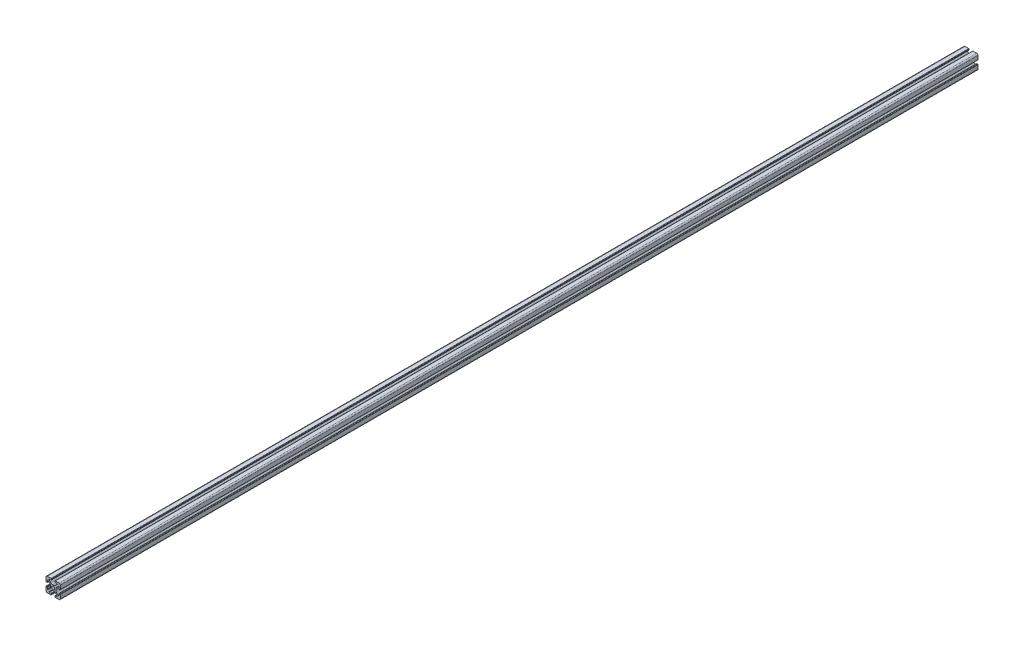
SolidWorks part; units mm, degrees
ref_plane "Front Plane" through (0, 0, 0) normal (0, 0, 1) x (1, 0, 0)
ref_plane "Top Plane" through (0, 0, 0) normal (0, 1, 0) x (1, 0, 0)
ref_plane "Right Plane" through (0, 0, 0) normal (1, 0, 0) x (0, 0, -1)
sketch "Sketch2" plane through (0, 0, 0) normal (0, 0, 1) x (1, 0, 0)
  line L0 (0, 10) -> (0, -10) construction
  line L1 (-10, 0) -> (10, 0) construction
  line L2 (2.5, -10) -> (10, -10)
  line L3 (10, -10) -> (10, -2.5)
  line L4 (2.5, -10) -> (2.5, -7.9246)
  line L5 (2.5, -7.9246) -> (6.4571, -7.9246)
  line L6 (6.4571, -7.9246) -> (2.1325, -3.6)
  line L7 (0, 0) -> (10, -10) construction
  line L8 (10, -2.5) -> (7.9246, -2.5)
  line L9 (7.9246, -2.5) -> (7.9246, -6.4571)
  line L10 (7.9246, -6.4571) -> (3.6, -2.1325)
  line L11 (5.7623, -4.2948) -> (4.2948, -5.7623) construction
  circle A0 centre (0, 0) radius 2.15
  arc A1 (5.25, -7.9246) -> (5.6036, -7.0711) centre (5.25, -7.4246) ccw construction
  point P8 (0, -3.6)
  point P16 (5.0286, -5.0286)
  dimension "Center Hole Diameter" = 4.3
  dimension "D3" = 0.5
  dimension "Rail Height" = 20
  dimension "Rail Width" = 20
  dimension "T-Slot Width" = 5
  dimension "Slot Depth" = 6.4
  dimension "Slot Inner Width" = 11.5
sketch "Sketch3" plane through (0, 0, 0) normal (1, 0, 0) x (0, 0, -1)
  line L0 (-640, -10) -> (640, -10) construction
  line L1 (-614.6, 0) -> (614.6, 0) construction
  line L2 (0, 10) -> (0, -10) construction
  line L3 (0, 10) -> (0, -10) construction
  point P6 (-614.6, 0)
  point P8 (614.6, 0)
  dimension "Length" = 1280
  dimension "D1" = 25.4
sketch "Sketch4" plane through (0, 0, 0) normal (0, 0, 1) x (1, 0, 0)
  line L0 (3, -10) -> (8.25, -10)
  line L1 (2.5, -10) -> (10, -10) construction
  line L2 (2.5, -10) -> (2.5, -7.9246) construction
  line L3 (2.5, -7.9246) -> (6.4571, -7.9246) construction
  line L4 (2.5, -8.4246) -> (2.5, -9.5)
  line L5 (3, -7.9246) -> (5.25, -7.9246)
  line L6 (0, -3.6) -> (0.8898, -3.6)
  line L7 (6.4571, -7.9246) -> (2.1325, -3.6) construction
  line L8 (3.0112, -4.4787) -> (5.6036, -7.0711)
  line L9 (10, -10) -> (10, -2.5) construction
  line L10 (7.9246, -6.4571) -> (3.6, -2.1325) construction
  line L11 (7.9246, -2.5) -> (7.9246, -6.4571) construction
  line L12 (7.9246, -5.25) -> (7.9246, -3)
  line L13 (10, -2.5) -> (7.9246, -2.5) construction
  line L14 (8.4246, -2.5) -> (9.5, -2.5)
  line L15 (10, -3) -> (10, -8.25)
  line L16 (7.0711, -5.6036) -> (4.4787, -3.0112)
  line L17 (3.6, 0) -> (3.6, -0.8898)
  line L18 (-10, 0) -> (10, 0) construction
  line L19 (0, -3.6) -> (0, -2.15)
  line L20 (0, 10) -> (0, -10) construction
  line L21 (3.6, 0) -> (2.15, 0)
  arc A0 (2.5, -9.5) -> (3, -10) centre (3, -9.5) ccw
  arc A1 (5.25, -7.9246) -> (5.6036, -7.0711) centre (5.25, -7.4246) ccw construction
  arc A2 (2.5, -8.4246) -> (3, -7.9246) centre (3, -8.4246) cw
  arc A3 (5.25, -7.9246) -> (5.6036, -7.0711) centre (5.25, -7.4246) ccw
  arc A4 (0.8898, -3.6) -> (3.0112, -4.4787) centre (0.8898, -6.6) cw
  arc A5 (8.25, -10) -> (10, -8.25) centre (8.25, -8.25) ccw
  arc A6 (7.0711, -5.6036) -> (7.9246, -5.25) centre (7.4246, -5.25) ccw
  arc A7 (7.9246, -3) -> (8.4246, -2.5) centre (8.4246, -3) cw
  arc A8 (9.5, -2.5) -> (10, -3) centre (9.5, -3) cw
  arc A9 (4.4787, -3.0112) -> (3.6, -0.8898) centre (6.6, -0.8898) cw
  circle A10 centre (0, 0) radius 2.15 construction
  arc A11 (0, -2.15) -> (2.15, 0) centre (0, 0) ccw
  dimension "D1" = 1.75
  dimension "D2" = 3
extrude "Boss-Extrude1" add sketch "Sketch4" along normal mid plane 1280
mirror "Mirror1" about plane through (0, 0, 0) normal (1, 0, 0) of bodies 134
mirror "Mirror2" about plane through (0, 0, 0) normal (0, 1, 0) of bodies 135
equation "\"D3@Sketch2\"=\"T-Slot Width@Sketch2\"*0.1"
equation "\"D1@Sketch4\"=\"D3@Sketch2\"*3.5"
equation "\"D2@Sketch4\"=\"D3@Sketch2\"*6"
equation "\"D1@Boss-Extrude1\"=\"Length@Sketch3\""
